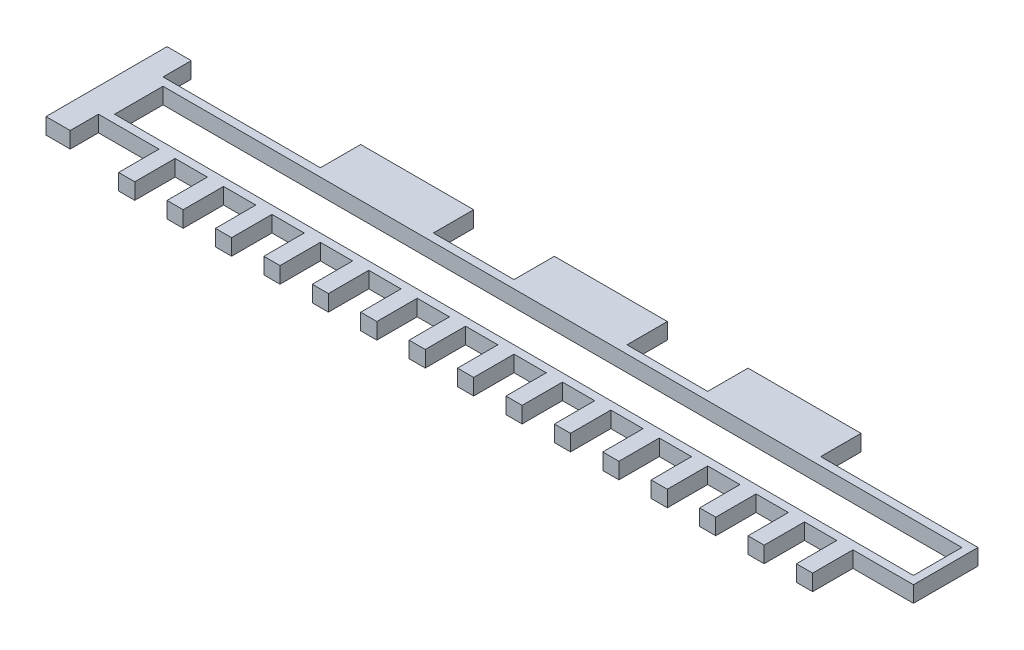
SolidWorks part; units mm, degrees
ref_plane "Front Plane" through (0, 0, 0) normal (0, 0, 1) x (1, 0, 0)
ref_plane "Top Plane" through (0, 0, 0) normal (0, 1, 0) x (1, 0, 0)
ref_plane "Right Plane" through (0, 0, 0) normal (1, 0, 0) x (0, 0, -1)
sketch "Sketch1" plane through (0, 0, 0) normal (0, 1, 0) x (1, 0, 0)
  line L0 (-50.5, 4) -> (-50.5, -4)
  line L1 (-49.5, 3) -> (49.5, 3)
  line L2 (-49.5, 3) -> (-49.5, -3)
  line L3 (-49.5, -3) -> (49.5, -3)
  line L4 (49.5, 3) -> (49.5, -3)
  line L5 (-49.5, 3) -> (49.5, -3) construction
  line L6 (-49.5, -3) -> (49.5, 3) construction
  line L7 (-50.5, -4) -> (50.5, -4)
  line L8 (50.5, 4) -> (50.5, -4)
  line L9 (-50.5, 4) -> (50.5, 4)
  point P0 (0, 0)
  dimension "D1" = 6
  dimension "D2" = 99
  dimension "D3" = 1
extrude "Boss-Extrude1" add sketch "Sketch1" along normal blind 2
sketch "Sketch2" plane through (0, 0, 0) normal (0, 1, 0) x (1, 0, 0)
  line L0 (-52, 0) -> (-35.8315, 0) construction
  line L1 (-50.5, 4) -> (-50.5, -4) construction
  line L2 (-53.5, 7.5) -> (-50.5, 7.5)
  line L3 (-53.5, 7.5) -> (-53.5, -7.5)
  line L4 (-53.5, -7.5) -> (-50.5, -7.5)
  line L5 (-50.5, 7.5) -> (-50.5, -7.5)
  line L6 (-53.5, 7.5) -> (-50.5, -7.5) construction
  line L7 (-53.5, -7.5) -> (-50.5, 7.5) construction
  line L8 (-42, 10.6202) -> (-42, -13.5508) construction
  line L9 (-49.5, 3) -> (-49.5, -3) construction
  line L10 (-50.5, -4) -> (50.5, -4) construction
  line L11 (-43, -9) -> (-41, -9)
  line L12 (-43, -9) -> (-43, -4)
  line L13 (-43, -4) -> (-41, -4)
  line L14 (-41, -9) -> (-41, -4)
  line L15 (-43, -9) -> (-41, -4) construction
  line L16 (-43, -4) -> (-41, -9) construction
  line L17 (-37, -9) -> (-37, -4)
  line L18 (-37, -9) -> (-35, -9)
  line L19 (-35, -9) -> (-35, -4)
  line L20 (-37, -4) -> (-35, -4)
  line L21 (-31, -9) -> (-31, -4)
  line L22 (-31, -9) -> (-29, -9)
  line L23 (-29, -9) -> (-29, -4)
  line L24 (-31, -4) -> (-29, -4)
  line L25 (-25, -9) -> (-25, -4)
  line L26 (-25, -9) -> (-23, -9)
  line L27 (-23, -9) -> (-23, -4)
  line L28 (-25, -4) -> (-23, -4)
  line L29 (-19, -9) -> (-19, -4)
  line L30 (-19, -9) -> (-17, -9)
  line L31 (-17, -9) -> (-17, -4)
  line L32 (-19, -4) -> (-17, -4)
  line L33 (-13, -9) -> (-13, -4)
  line L34 (-13, -9) -> (-11, -9)
  line L35 (-11, -9) -> (-11, -4)
  line L36 (-13, -4) -> (-11, -4)
  line L37 (-7, -9) -> (-7, -4)
  line L38 (-7, -9) -> (-5, -9)
  line L39 (-5, -9) -> (-5, -4)
  line L40 (-7, -4) -> (-5, -4)
  line L41 (-1, -9) -> (-1, -4)
  line L42 (-1, -9) -> (1, -9)
  line L43 (1, -9) -> (1, -4)
  line L44 (-1, -4) -> (1, -4)
  line L45 (5, -9) -> (5, -4)
  line L46 (5, -9) -> (7, -9)
  line L47 (7, -9) -> (7, -4)
  line L48 (5, -4) -> (7, -4)
  line L49 (11, -9) -> (11, -4)
  line L50 (11, -9) -> (13, -9)
  line L51 (13, -9) -> (13, -4)
  line L52 (11, -4) -> (13, -4)
  line L53 (17, -9) -> (17, -4)
  line L54 (17, -9) -> (19, -9)
  line L55 (19, -9) -> (19, -4)
  line L56 (17, -4) -> (19, -4)
  line L57 (23, -9) -> (23, -4)
  line L58 (23, -9) -> (25, -9)
  line L59 (25, -9) -> (25, -4)
  line L60 (23, -4) -> (25, -4)
  line L61 (29, -9) -> (29, -4)
  line L62 (29, -9) -> (31, -9)
  line L63 (31, -9) -> (31, -4)
  line L64 (29, -4) -> (31, -4)
  line L65 (35, -9) -> (35, -4)
  line L66 (35, -9) -> (37, -9)
  line L67 (37, -9) -> (37, -4)
  line L68 (35, -4) -> (37, -4)
  line L69 (41, -9) -> (41, -4)
  line L70 (41, -9) -> (43, -9)
  line L71 (43, -9) -> (43, -4)
  line L72 (41, -4) -> (43, -4)
  line L77 (47, -9) -> (47, -4) [skipped]
  line L78 (47, -4) -> (49, -4) [skipped]
  line L79 (49, -9) -> (49, -4) [skipped]
  line L80 (47, -9) -> (49, -9) [skipped]
  line L81 (-24, 13.7085) -> (-24, -28.4338) construction
  line L82 (50.5, 4) -> (-50.5, 4) construction
  line L83 (-31, 9) -> (-17, 9)
  line L84 (-31, 9) -> (-31, 4)
  line L85 (-31, 4) -> (-17, 4)
  line L86 (-17, 9) -> (-17, 4)
  line L87 (-31, 9) -> (-17, 4) construction
  line L88 (-31, 4) -> (-17, 9) construction
  line L89 (-7, 9) -> (-7, 4)
  line L90 (-7, 9) -> (7, 9)
  line L91 (7, 9) -> (7, 4)
  line L92 (-7, 4) -> (7, 4)
  line L93 (17, 9) -> (17, 4)
  line L94 (17, 9) -> (31, 9)
  line L95 (31, 9) -> (31, 4)
  line L96 (17, 4) -> (31, 4)
  point P13 (-42, -6.5)
  point P78 (-24, 6.5)
  dimension "D1" = 3
  dimension "D2" = 15
  dimension "D3" = 7.5
  dimension "D4" = 2
  dimension "D5" = 5
  dimension "D7" = 25.5
  dimension "D8" = 14
  dimension "D9" = 5
  dimension "D6" = 16
  dimension "D10" = 3
extrude "Boss-Extrude2" add sketch "Sketch2" along normal blind 2
